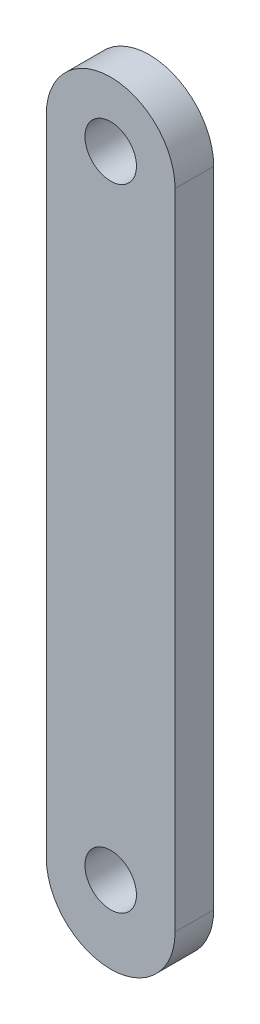
SolidWorks part; units mm, degrees
ref_plane "Front Plane" through (0, 0, 0) normal (0, 0, 1) x (1, 0, 0)
ref_plane "Top Plane" through (0, 0, 0) normal (0, 1, 0) x (1, 0, 0)
ref_plane "Right Plane" through (0, 0, 0) normal (1, 0, 0) x (0, 0, -1)
sketch "Sketch1" plane through (0, 0, 0) normal (0, 0, 1) x (1, 0, 0)
  line L0 (0, 25) -> (0, -25) construction
  line L1 (5, 25) -> (5, -25)
  line L2 (-5, 25) -> (-5, -25)
  arc A0 (5, 25) -> (-5, 25) centre (0, 25) ccw
  arc A1 (-5, -25) -> (5, -25) centre (0, -25) ccw
  circle A2 centre (0, 25) radius 2
  circle A3 centre (0, -24) radius 2
  point P3 (0, 0)
  point P12 (0, 0)
  point P13 (0, 0)
  dimension "D1" = 5
  dimension "D3" = 4
  dimension "D2" = 50
  dimension "D4" = 49
  dimension "D5" = 1
extrude "Boss-Extrude1" add sketch "Sketch1" along normal blind 3
